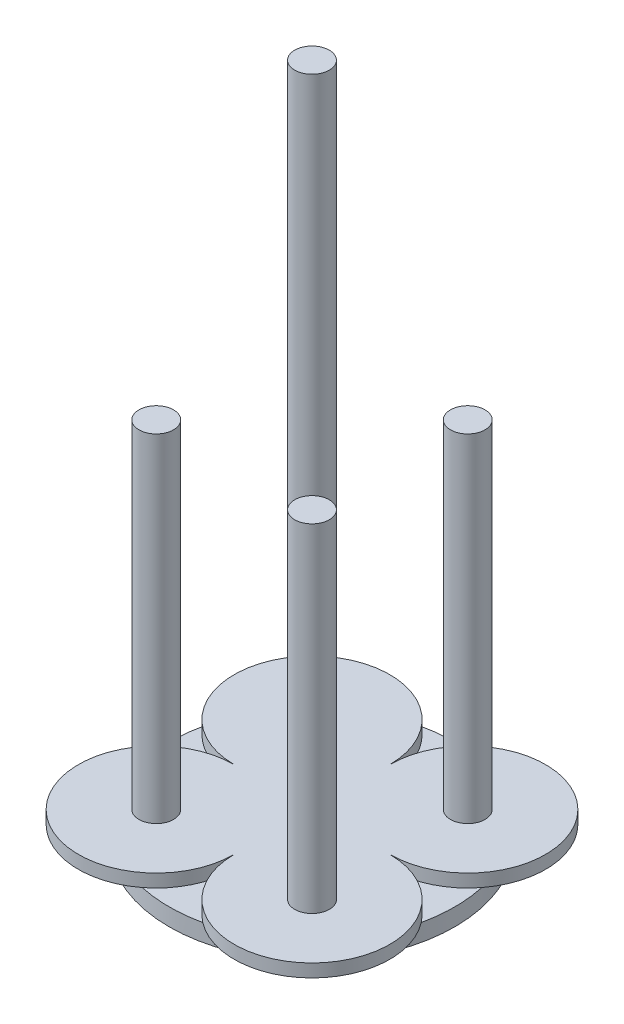
SolidWorks part; units mm, degrees
ref_plane "Front Plane" through (0, 0, 0) normal (0, 0, 1) x (1, 0, 0)
ref_plane "Top Plane" through (0, 0, 0) normal (0, 1, 0) x (1, 0, 0)
ref_plane "Right Plane" through (0, 0, 0) normal (1, 0, 0) x (0, 0, -1)
sketch "Sketch1" plane through (0, 0, 0) normal (0, 1, 0) x (1, 0, 0)
  circle A0 centre (0, 0) radius 33
  dimension "D1" = 66
extrude "Boss-Extrude1" add sketch "Sketch1" along normal blind 4
sketch "Sketch2" plane through (0, 4, 0) normal (0, 1, 0) x (1, 0, 0)
  line L0 (0, 52.9391) -> (0, 0) construction
  line L1 (-61.9893, 0) -> (-18, 0) construction
  line L2 (18, 0) -> (93.9652, 0) construction
  line L3 (0, -18) -> (0, -50.1265) construction
  arc A0 (18, 0) -> (0, 18) centre (18, 18) ccw
  arc A1 (0, -18) -> (18, 0) centre (18, -18) ccw
  arc A2 (-18, 0) -> (0, -18) centre (-18, -18) ccw
  arc A3 (0, 18) -> (-18, 0) centre (-18, 18) ccw
  point P16 (0, 0)
  dimension "D1" = 36
  dimension "D2" = 4
extrude "Boss-Extrude2" add sketch "Sketch2" along normal blind 3
sketch "Sketch3" plane through (0, 7, 0) normal (0, 1, 0) x (1, 0, 0)
  circle A0 centre (-18, 18) radius 4
  circle A1 centre (18, 18) radius 4
  circle A2 centre (18, -18) radius 4
  circle A3 centre (-18, -18) radius 4
  point P12 (0, 0)
  dimension "D1" = 8
  dimension "D2" = 4
extrude "Boss-Extrude3" add sketch "Sketch3" along normal blind 78
sketch "Sketch4" plane through (0, 7, 0) normal (0, 1, 0) x (1, 0, 0)
  circle A0 centre (0, 0) radius 4
  dimension "D1" = 8
extrude "Boss-Extrude4" add sketch "Sketch4" along normal blind 150
